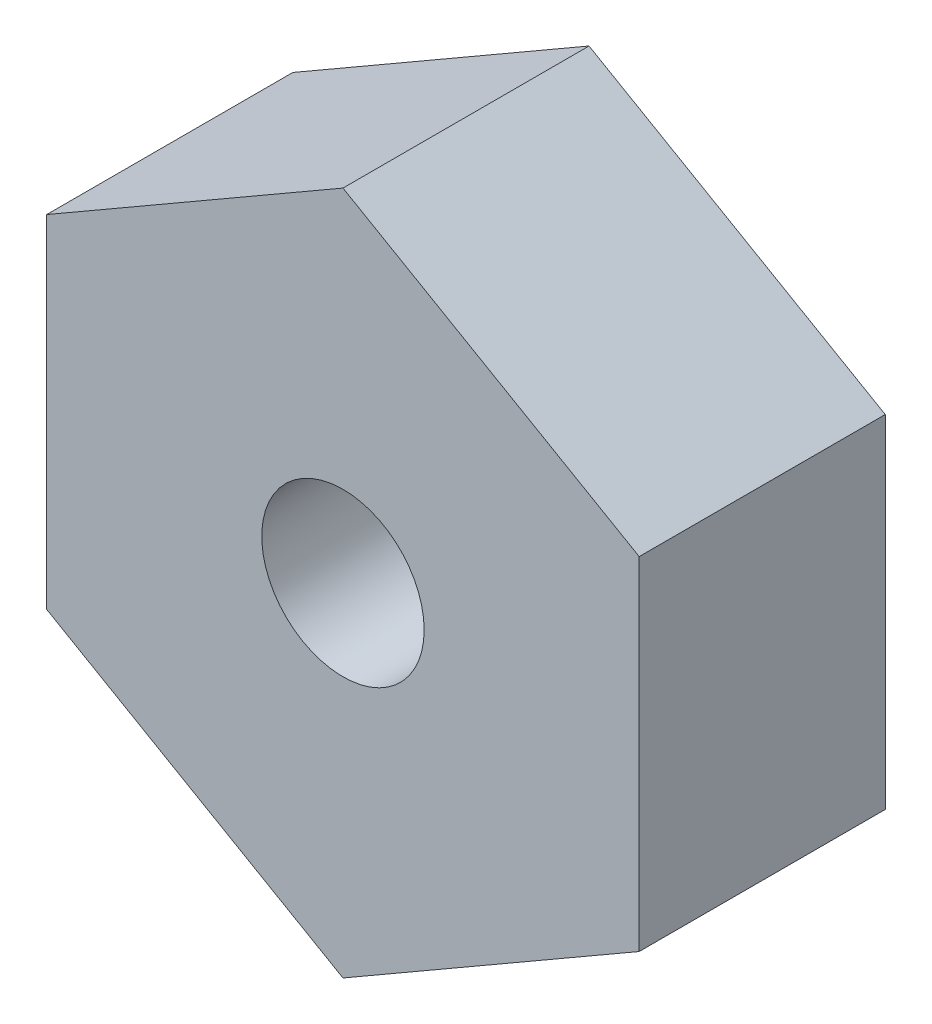
SolidWorks part; units mm, degrees
ref_plane "Front Plane" through (0, 0, 0) normal (0, 0, 1) x (1, 0, 0)
ref_plane "Top Plane" through (0, 0, 0) normal (0, 1, 0) x (1, 0, 0)
ref_plane "Right Plane" through (0, 0, 0) normal (1, 0, 0) x (0, 0, -1)
sketch "Sketch1" plane through (0, 0, 0) normal (0, 0, 1) x (1, 0, 0)
  line L1 (0, -6.95) -> (6.0189, -3.475)
  line L2 (6.0189, -3.475) -> (6.0189, 3.475)
  line L3 (6.0189, 3.475) -> (0, 6.95)
  line L4 (0, 6.95) -> (-6.0189, 3.475)
  line L5 (-6.0189, 3.475) -> (-6.0189, -3.475)
  line L6 (-6.0189, -3.475) -> (0, -6.95)
  circle A0 centre (0, 0) radius 6.0189 construction
  dimension "D1" = 13.9
extrude "Boss-Extrude1" add sketch "Sketch1" along normal blind 5
sketch "Sketch2" plane through (0, 0, 5) normal (0, 0, 1) x (1, 0, 0)
  circle A0 centre (0, 0) radius 1.65
  dimension "D1" = 3.3
extrude "Cut-Extrude1" cut sketch "Sketch2" against normal blind 10
